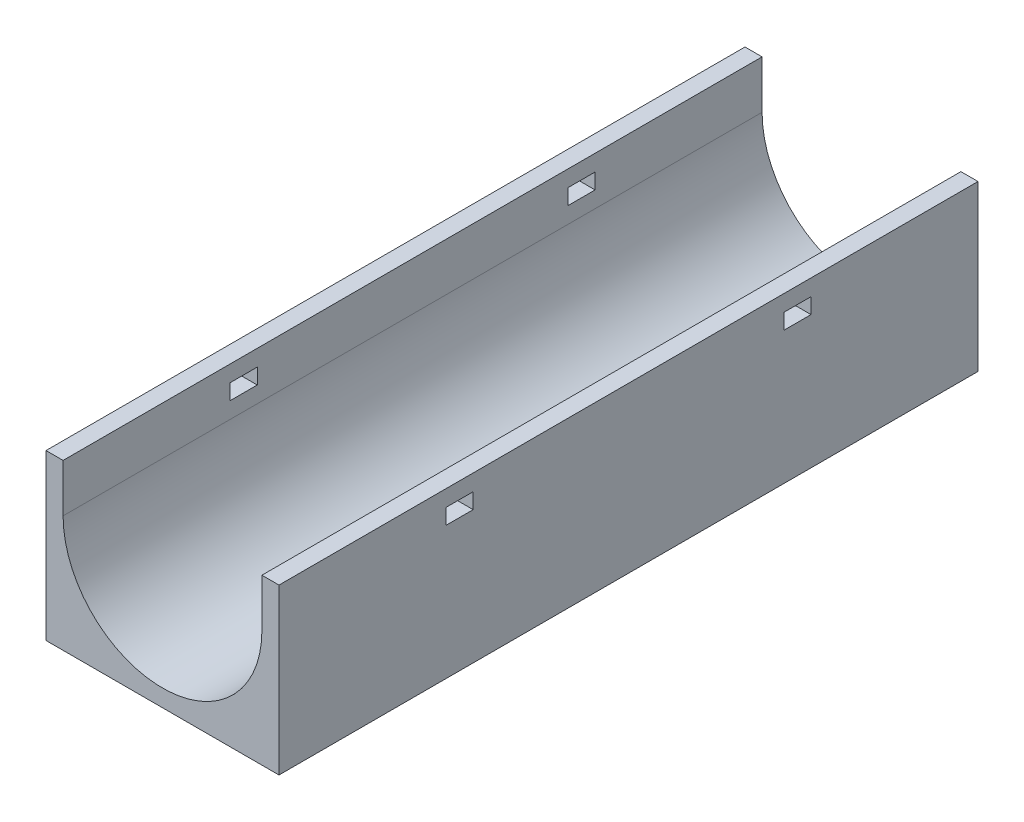
SolidWorks part; units mm, degrees
ref_plane "Front Plane" through (0, 0, 0) normal (0, 0, 1) x (1, 0, 0)
ref_plane "Top Plane" through (0, 0, 0) normal (0, 1, 0) x (1, 0, 0)
ref_plane "Right Plane" through (0, 0, 0) normal (1, 0, 0) x (0, 0, -1)
sketch "Sketch1" plane through (0, 0, 0) normal (0, 1, 0) x (1, 0, 0)
  line L1 (0, 0) -> (76.2, 0)
  line L2 (0, 0) -> (0, 228.6)
  line L3 (0, 228.6) -> (76.2, 228.6)
  line L4 (76.2, 0) -> (76.2, 228.6)
  dimension "D1" = 228.6
  dimension "D2" = 76.2
extrude "Boss-Extrude1" add sketch "Sketch1" along normal blind 38.1
sketch "Sketch2" plane through (0, 0, 0) normal (0, 0, 1) x (1, 0, 0)
  line L0 (0, 38.1) -> (76.2, 38.1) construction
  circle A0 centre (38.1, 38.1) radius 32.512
  dimension "D1" = 65.024
extrude "Cut-Extrude2" cut sketch "Sketch2" against normal through all contours A0
sketch "Sketch3" plane through (0, 0, 0) normal (0, 0, 1) x (1, 0, 0)
  line L1 (0, 38.1) -> (5.588, 38.1)
  line L2 (0, 38.1) -> (0, 53.8055)
  line L3 (0, 53.8055) -> (5.588, 53.8055)
  line L4 (5.588, 38.1) -> (5.588, 53.8055)
  line L5 (70.612, 38.1) -> (76.2, 38.1)
  line L6 (70.612, 38.1) -> (70.612, 53.8055)
  line L7 (70.612, 53.8055) -> (76.2, 53.8055)
  line L8 (76.2, 38.1) -> (76.2, 53.8055)
extrude "Boss-Extrude2" add sketch "Sketch3" against normal up to surface (228.6 mm away) up to face at (38.1, 19.9813, -228.6)
sketch "Sketch4" plane through (76.2, 0, 0) normal (1, 0, 0) x (0, 0, -1)
  line L5 (54.61, 48.4928) -> (63.5, 48.4928)
  line L6 (54.61, 43.4128) -> (63.5, 43.4128)
  line L8 (63.5, 48.4928) -> (63.5, 43.4128)
  line L9 (165.1, 48.4928) -> (165.1, 43.4128)
  line L10 (54.61, 48.4928) -> (54.61, 43.4128)
  line L11 (173.99, 48.4928) -> (173.99, 43.4128)
  line L17 (165.1, 48.4928) -> (173.99, 48.4928)
  line L19 (165.1, 43.4128) -> (173.99, 43.4128)
extrude "Cut-Extrude3" cut sketch "Sketch4" against normal through all
